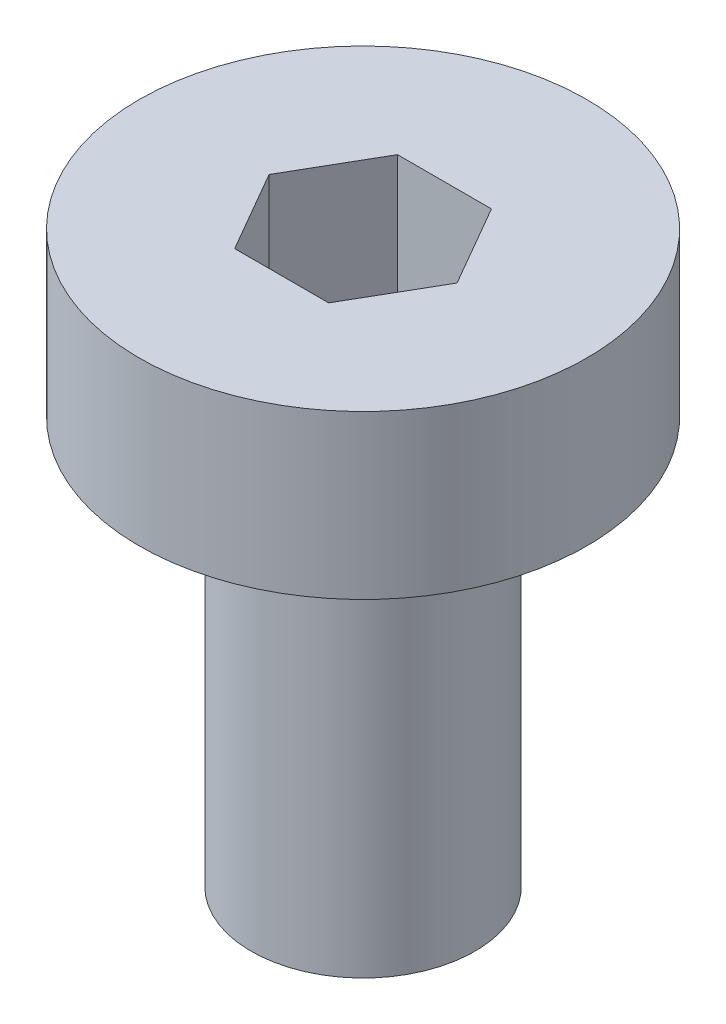
SolidWorks part; units mm, degrees
material "AISI 316 Stainless Steel Sheet (SS)"
ref_plane "Front Plane" through (0, 0, 0) normal (0, 0, 1) x (1, 0, 0)
ref_plane "Top Plane" through (0, 0, 0) normal (0, 1, 0) x (1, 0, 0)
ref_plane "Right Plane" through (0, 0, 0) normal (1, 0, 0) x (0, 0, -1)
sketch "Sketch1" plane through (0, 0, 0) normal (0, 0, 1) x (1, 0, 0)
  line L0 (0, 2) -> (-2.75, 2)
  line L1 (-2.75, 2) -> (-2.75, 0)
  line L2 (-2.75, 0) -> (-1.375, 0)
  line L3 (-1.375, 0) -> (-1.375, -5)
  line L4 (-1.375, -5) -> (0, -5)
  line L5 (0, -5) -> (0, 2)
  line L6 (0, -5) -> (0, -19.4894) construction
  dimension "D1" = 2.75
  dimension "D2" = 2
  dimension "D3" = 5.5
  dimension "D4" = 5
revolve "Revolve1" add sketch "Sketch1" angle 360 about L6
sketch "Sketch2" plane through (0, 2, 0) normal (0, 1, 0) x (1, 0, 0)
  line L1 (0.5774, -1) -> (1.1547, 0)
  line L2 (1.1547, 0) -> (0.5774, 1)
  line L3 (0.5774, 1) -> (-0.5774, 1)
  line L4 (-0.5774, 1) -> (-1.1547, 0)
  line L5 (-1.1547, 0) -> (-0.5774, -1)
  line L6 (-0.5774, -1) -> (0.5774, -1)
  circle A0 centre (0, 0) radius 1 construction
  dimension "D1" = 2
extrude "Cut-Extrude1" cut sketch "Sketch2" against normal blind 1.5
